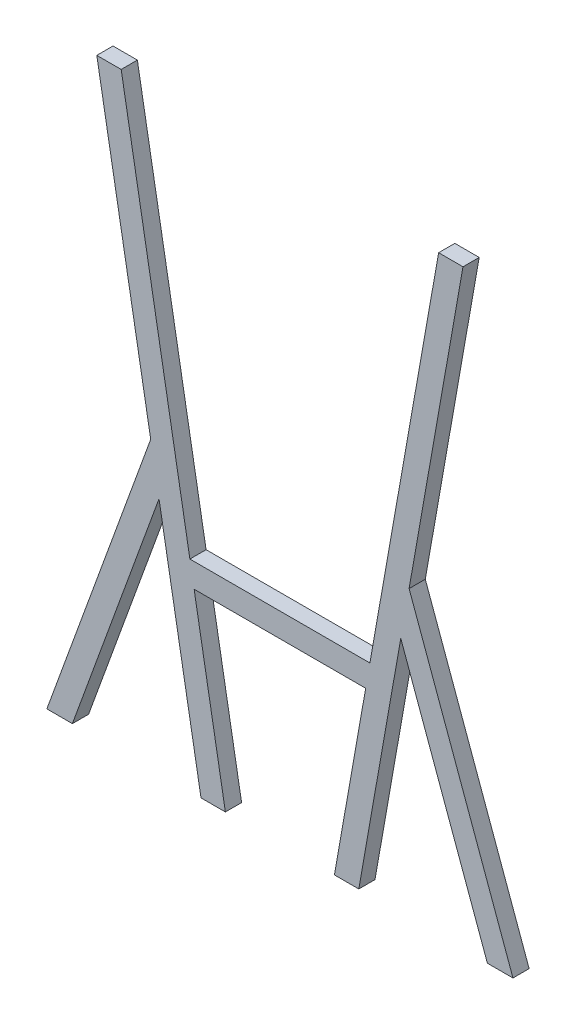
SolidWorks part; units mm, degrees
ref_plane "Plan de face" through (0, 0, 0) normal (0, 0, 1) x (1, 0, 0)
ref_plane "Plan de dessus" through (0, 0, 0) normal (0, 1, 0) x (1, 0, 0)
ref_plane "Plan de droite" through (0, 0, 0) normal (1, 0, 0) x (0, 0, -1)
sketch "Esquisse1" plane through (0, 0, 0) normal (0, 0, 1) x (1, 0, 0)
  line L0 (0, 0) -> (-173.6482, 984.8078)
  line L1 (-173.6482, 984.8078) -> (-133.0311, 984.8078)
  line L3 (40.6171, 0) -> (0, 0)
  line L4 (0, 0) -> (0, 66.5901) construction
  line L5 (40.6171, 0) -> (-11.4774, 295.4423)
  line L6 (-11.4774, 295.4423) -> (274.4165, 295.4423)
  line L7 (281.4695, 335.4423) -> (-18.5305, 335.4423)
  line L8 (-18.5305, 335.4423) -> (-133.0311, 984.8078)
  line L9 (131.4695, 295.4423) -> (131.4695, 335.4423) construction
  line L10 (262.9391, 0) -> (262.9391, 66.5901) construction
  line L11 (281.4695, 335.4423) -> (395.9702, 984.8078)
  line L12 (222.322, 0) -> (274.4165, 295.4423)
  line L13 (222.322, 0) -> (262.9391, 0)
  line L14 (436.5872, 984.8078) -> (395.9702, 984.8078)
  line L15 (262.9391, 0) -> (436.5872, 984.8078)
  dimension "D1" = 300
  dimension "D2" = 1000
  dimension "D3" = 10
  dimension "D4" = 40
  dimension "D5" = 40
  dimension "D6" = 300
extrude "Boss.-Extru.1" add sketch "Esquisse1" along normal blind 27
sketch "Esquisse2" plane through (0, 0, 27) normal (0, 0, 1) x (1, 0, 0)
  line L0 (-69.9489, 396.6998) -> (-214.3358, 0)
  line L1 (-173.6482, 984.8078) -> (0, 0) construction
  line L2 (-214.3358, 0) -> (-256.9029, 0)
  line L3 (-256.9029, 0) -> (-83.8407, 475.4845)
  line L4 (-83.8407, 475.4845) -> (-69.9489, 396.6998)
  line L5 (0, 0) -> (40.6171, 0) construction
  line L6 (40.6171, 0) -> (222.322, 0) construction
  line L7 (131.4695, 0) -> (131.4695, 747.5835) construction
  line L8 (346.7798, 475.4845) -> (332.8879, 396.6998)
  line L9 (519.842, 0) -> (346.7798, 475.4845)
  line L10 (477.2749, 0) -> (519.842, 0)
  line L11 (332.8879, 396.6998) -> (477.2749, 0)
  point P19 (-77.6088, 440.1413)
  dimension "D1" = 40
  dimension "D2" = 506
  dimension "D3" = 30
extrude "Boss.-Extru.2" add sketch "Esquisse2" against normal up to vertex (27 mm away) up to point (0, 0, 0)
